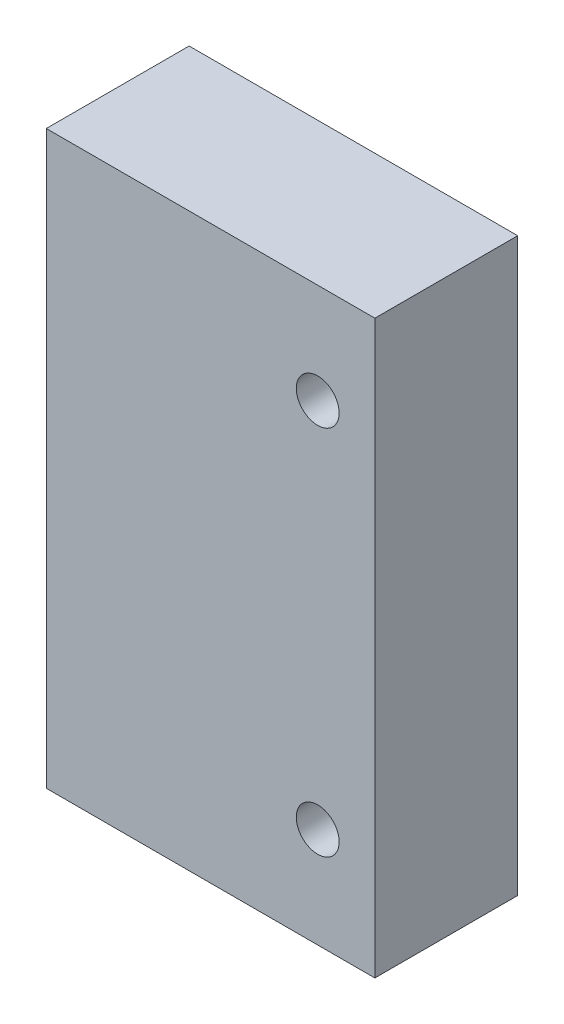
SolidWorks part; units mm, degrees
ref_plane "前视基准面" through (0, 0, 0) normal (0, 0, 1) x (1, 0, 0)
ref_plane "上视基准面" through (0, 0, 0) normal (0, 1, 0) x (1, 0, 0)
ref_plane "右视基准面" through (0, 0, 0) normal (1, 0, 0) x (0, 0, -1)
sketch "草图1" plane through (0, 0, 0) normal (0, 0, 1) x (1, 0, 0)
  line L1 (-11.5, 20) -> (11.5, 20)
  line L2 (-11.5, 20) -> (-11.5, -20)
  line L3 (-11.5, -20) -> (11.5, -20)
  line L4 (11.5, 20) -> (11.5, -20)
  line L5 (-11.5, 20) -> (11.5, -20) construction
  line L6 (-11.5, -20) -> (11.5, 20) construction
  circle A0 centre (7.5, 13) radius 1.5
  circle A1 centre (7.5, -13) radius 1.5
  point P0 (0, 0)
  point P10 (0, 0)
  dimension "D3" = 3
  dimension "D1" = 40
  dimension "D2" = 23
  dimension "D4" = 13
  dimension "D5" = 13
  dimension "D6" = 4
extrude "凸台-拉伸1" add sketch "草图1" along normal blind 10
